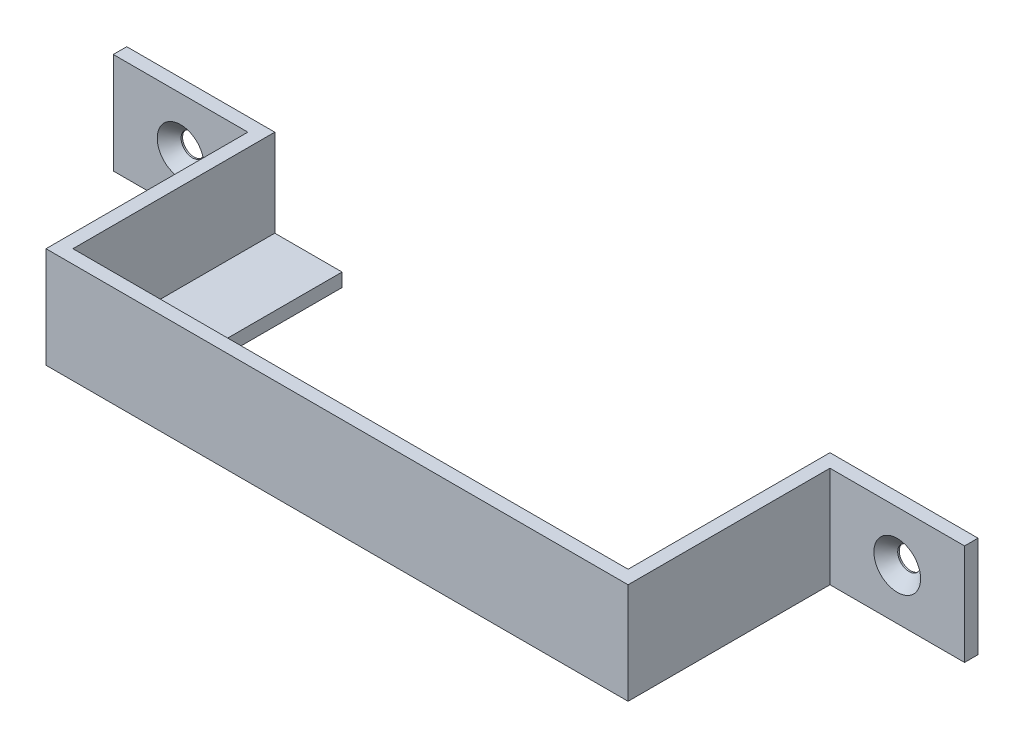
SolidWorks part; units mm, degrees
ref_plane "Oben" through (0, 0, 0) normal (0, 0, 1) x (1, 0, 0)
ref_plane "Vorne" through (0, 0, 0) normal (0, 1, 0) x (1, 0, 0)
ref_plane "Rechts" through (0, 0, 0) normal (1, 0, 0) x (0, 0, -1)
sketch "Skizze1" plane through (0, 0, 0) normal (0, 1, 0) x (1, 0, 0)
  line L0 (0, 0) -> (22, 0)
  line L1 (22, 0) -> (22, -30)
  line L2 (22, -30) -> (104.5, -30)
  line L3 (104.5, -30) -> (104.5, 0)
  line L4 (104.5, 0) -> (126.5, 0)
  line L5 (126.5, 0) -> (126.5, -2)
  line L6 (126.5, -2) -> (106.5, -2)
  line L7 (106.5, -2) -> (106.5, -32)
  line L8 (106.5, -32) -> (20, -32)
  line L9 (20, -32) -> (20, -2)
  line L10 (20, -2) -> (0, -2)
  line L11 (0, -2) -> (0, 0)
extrude "Aufsatz-Linear austragen1" add sketch "Skizze1" along normal blind 15
sketch "Skizze2" plane through (0, 0, 0) normal (0, -1, 0) x (1, 0, 0)
  line L0 (22, 0) -> (32, 0)
  line L1 (32, 0) -> (32, 25)
  line L2 (32, 25) -> (94.5, 25)
  line L3 (94.5, 25) -> (94.5, 0)
  line L4 (94.5, 0) -> (104.5, 0)
  line L5 (104.5, 0) -> (104.5, 30)
  line L6 (104.5, 30) -> (22, 30)
  line L7 (22, 30) -> (22, 0)
extrude "Aufsatz-Linear austragen2" add sketch "Skizze2" against normal blind 2
sketch "Skizze3" plane through (0, 0, 2) normal (0, 0, 1) x (1, 0, 0)
  line L1 (0, 15) -> (20, 15)
  line L2 (0, 15) -> (0, 0)
  line L3 (0, 0) -> (20, 0)
  line L4 (20, 15) -> (20, 0)
  line L5 (0, 15) -> (20, 0) construction
  line L6 (0, 0) -> (20, 15) construction
  line L7 (106.5, 15) -> (126.5, 15)
  line L8 (106.5, 15) -> (106.5, 0)
  line L9 (106.5, 0) -> (126.5, 0)
  line L10 (126.5, 15) -> (126.5, 0)
  line L11 (106.5, 15) -> (126.5, 0) construction
  line L12 (106.5, 0) -> (126.5, 15) construction
  point P4 (10, 7.5)
  point P11 (116.5, 7.5)
hole_wizard "Formsenkung für M3 Senkschraube mit Innensechskant1" positions "Skizze4" profile "Skizze5" countersink size "M3" standard "DIN"
sketch "Skizze4" plane through (0, 0, 2) normal (0, 0, 1) x (1, 0, 0)
  point P0 (10, 7.5)
  point P3 (116.5, 7.5)
sketch "Skizze5" plane through (10, 7.5, 2) normal (1, 0, 0) x (0, -1, 0)
  line L0 (0, 0) -> (0, 11.0215)
  line L1 (0, 11.0215) -> (1.7, 10)
  line L2 (1.7, 10) -> (1.7, 1.77)
  line L3 (1.7, 1.77) -> (3.47, 0)
  line L5 (3.47, 0) -> (0, 0)
  line L6 (-1.7, 1.77) -> (-3.47, 0) construction
  line L10 (0, 11.0215) -> (-1.7, 10) construction
  line L11 (0, -6.35) -> (0, 107.95) construction
  dimension "Bohrerdurchmesser" = 3.4
  dimension "Bohrungstiefe" = 10
  dimension "Senkdurchmesser (Oben)" = 6.94
  dimension "Senkwinkel (Oben)" = 90
  dimension "Spitzenwinkel" = 118
